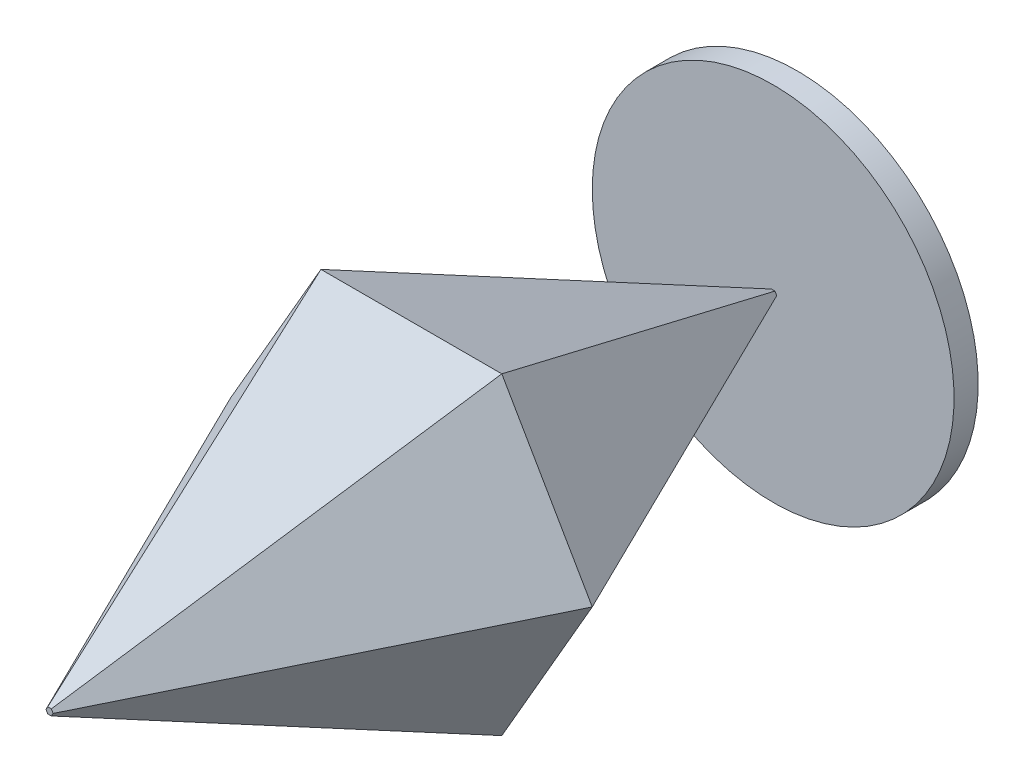
SolidWorks part; units mm, degrees
ref_plane "Plan de face" through (0, 0, 0) normal (0, 0, 1) x (1, 0, 0)
ref_plane "Plan de dessus" through (0, 0, 0) normal (0, 1, 0) x (1, 0, 0)
ref_plane "Plan de droite" through (0, 0, 0) normal (1, 0, 0) x (0, 0, -1)
sketch "Esquisse1" plane through (0, 0, 0) normal (0, 0, 1) x (1, 0, 0)
  line L1 (15, 0) -> (7.5, 12.9904)
  line L2 (7.5, 12.9904) -> (-7.5, 12.9904)
  line L3 (-7.5, 12.9904) -> (-15, 0)
  line L4 (-15, 0) -> (-7.5, -12.9904)
  line L5 (-7.5, -12.9904) -> (7.5, -12.9904)
  line L6 (7.5, -12.9904) -> (15, 0)
  circle A0 centre (0, 0) radius 12.9904 construction
  dimension "D1" = 15
extrude "Boss.-Extru.1" add sketch "Esquisse1" along normal blind 30 draft 23
mirror "Symétrie1" about plane through (0, 0, 0) normal (0, 0, 1) of "Boss.-Extru.1"
sketch "Esquisse2" plane through (0, 0, -30) normal (0, 0, -1) x (-1, 0, 0)
  circle A0 centre (0, 0) radius 15
extrude "Boss.-Extru.2" add sketch "Esquisse2" along normal blind 2
